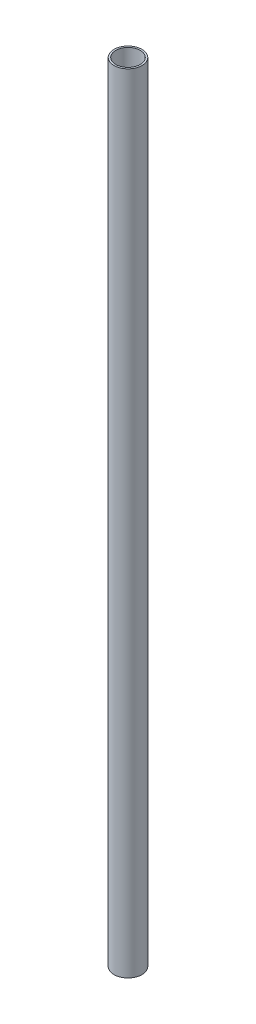
SolidWorks part; units mm, degrees
ref_plane "Front Plane" through (0, 0, 0) normal (0, 0, 1) x (1, 0, 0)
ref_plane "Top Plane" through (0, 0, 0) normal (0, 1, 0) x (1, 0, 0)
ref_plane "Right Plane" through (0, 0, 0) normal (1, 0, 0) x (0, 0, -1)
sketch "Sketch1" plane through (0, 0, 0) normal (0, 1, 0) x (1, 0, 0)
  circle A0 centre (0, 0) radius 3.5
  circle A1 centre (0, 0) radius 4
  dimension "D1" = 8
  dimension "D2" = 0.5
extrude "Boss-Extrude1" add sketch "Sketch1" along normal blind 225
